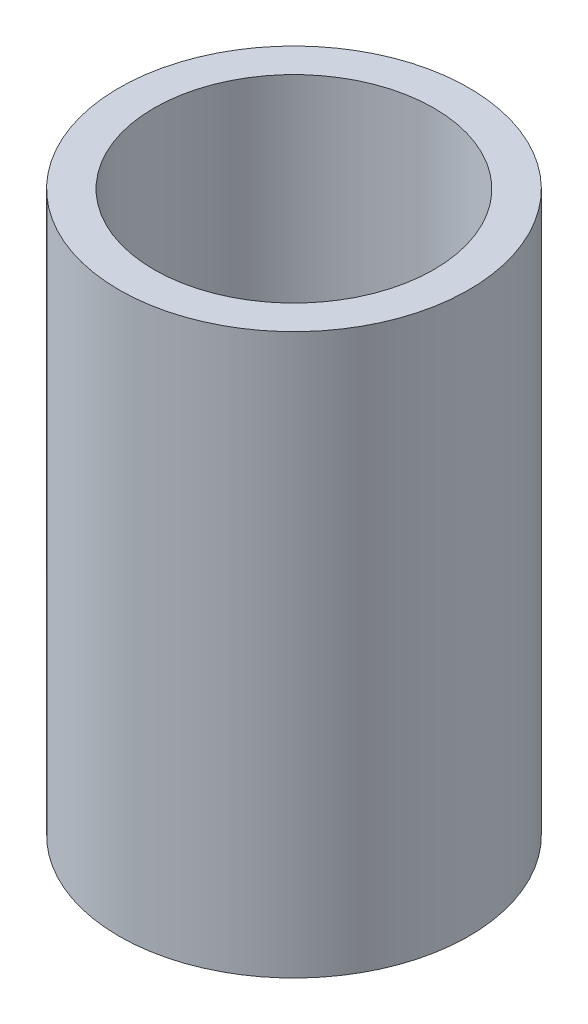
SolidWorks part; units mm, degrees
ref_plane "Front Plane" through (0, 0, 0) normal (0, 0, 1) x (1, 0, 0)
ref_plane "Top Plane" through (0, 0, 0) normal (0, 1, 0) x (1, 0, 0)
ref_plane "Right Plane" through (0, 0, 0) normal (1, 0, 0) x (0, 0, -1)
sketch "Sketch1" plane through (0, 0, 0) normal (0, 1, 0) x (1, 0, 0)
  circle A0 centre (0, 0) radius 7.5
  dimension "D1" = 15
extrude "Boss-Extrude1" add sketch "Sketch1" along normal blind 24
sketch "Sketch2" plane through (0, 24, 0) normal (0, 1, 0) x (1, 0, 0)
  circle A0 centre (0, 0) radius 6
  dimension "D1" = 12
extrude "Cut-Extrude1" cut sketch "Sketch2" against normal up to next
